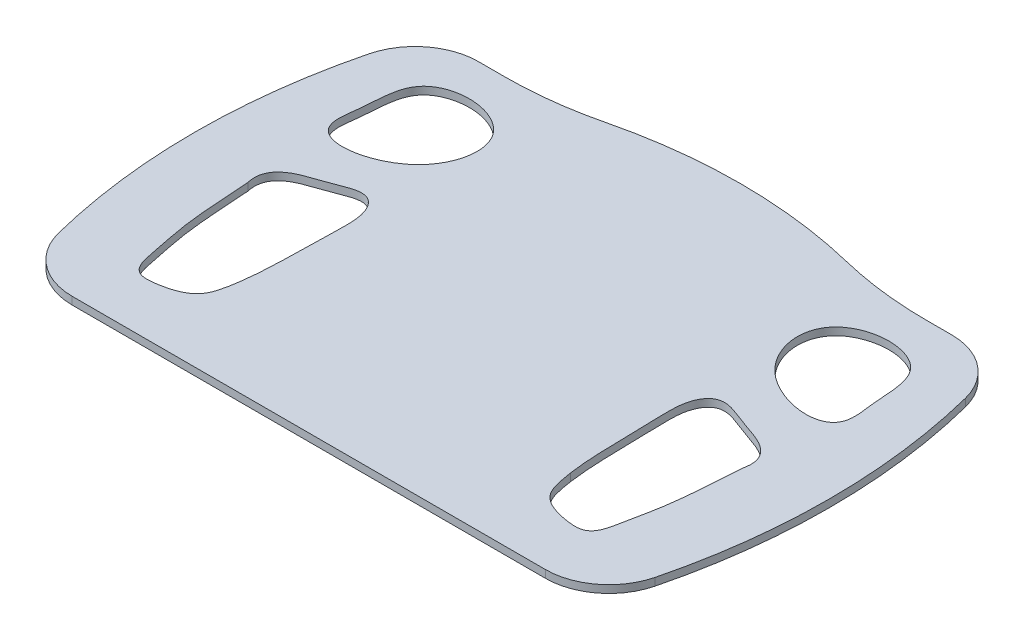
SolidWorks part; units mm, degrees
ref_plane "前视基准面" through (0, 0, 0) normal (0, 0, 1) x (1, 0, 0)
ref_plane "上视基准面" through (0, 0, 0) normal (0, 1, 0) x (1, 0, 0)
ref_plane "右视基准面" through (0, 0, 0) normal (1, 0, 0) x (0, 0, -1)
other "Configuration Table"
sketch "草图1" plane through (0, 0, 0) normal (0, 1, 0) x (1, 0, 0)
  line L0 (94.3902, -85.9727) -> (-91.9583, -85.9727)
  line L1 (-91.9583, 74.0273) -> (-81.8503, 74.0273)
  line L2 (84.2822, 74.0273) -> (94.3902, 74.0273)
  arc A0 (94.3902, -85.9727) -> (118.6318, -67.0839) centre (94.3902, -60.9727) ccw
  arc A1 (-116.1999, -67.0839) -> (-91.9583, -85.9727) centre (-91.9583, -60.9727) ccw
  arc A2 (-116.1999, 55.1384) -> (-116.1999, -67.0839) centre (126.2159, -5.9727) ccw
  arc A3 (-91.9583, 74.0273) -> (-116.1999, 55.1384) centre (-91.9583, 49.0273) ccw
  arc A4 (-81.8503, 74.0273) -> (-46.2505, 78.313) centre (-81.8503, 224.0273) ccw
  arc A5 (48.6824, 78.313) -> (-46.2505, 78.313) centre (1.2159, -115.9727) ccw
  arc A6 (48.6824, 78.313) -> (84.2822, 74.0273) centre (84.2822, 224.0273) ccw
  arc A7 (118.6318, 55.1384) -> (94.3902, 74.0273) centre (94.3902, 49.0273) ccw
  arc A8 (118.6318, -67.0839) -> (118.6318, 55.1384) centre (-123.7841, -5.9727) ccw
  spline S0 degree 3 poles (66.2811, 20.5807) (60.5847, 52.9198) (82.8802, 61.3288) (95.3724, 57.693) (102.1843, 48.7306) (101.6256, 38.7803) (103.3639, 27.4794) (102.123, 14.4904) (66.2811, 20.5807) (60.5847, 52.9198) (82.8802, 61.3288) knots -0.58846 -0.515599 -0.249223 0 0.116916 0.219737 0.24839 0.386216 0.41154 0.484401 0.750777 1 1.116916 1.219737 1.24839 only from (68.9861, 54.0529) to (68.9861, 54.0529)
  spline S1 degree 3 poles (66.3784, -48.0704) (66.5131, -48.9639) (66.7845, -50.7507) (67.2066, -52.9697) (67.6381, -54.7261) (68.0285, -56.0263) (68.5147, -57.2927) (69.1248, -58.5037) (69.878, -59.6297) (70.7809, -60.64) (71.6384, -61.376) (72.373, -61.9014) (72.945, -62.265) (73.5345, -62.5993) (74.1387, -62.9062) (74.7553, -63.1874) (75.3821, -63.4451) (76.0175, -63.6812) (76.8741, -63.9697) (77.9594, -64.2861) (79.0571, -64.5561) (79.9401, -64.7497) (80.6044, -64.8843) (81.2708, -65.0088) (82.1619, -65.1601) (83.0572, -65.2868) (83.9569, -65.3776) (84.6336, -65.4235) (85.3116, -65.4416) (85.9897, -65.4257) (86.6662, -65.3691) (87.3361, -65.2628) (87.9925, -65.0972) (88.6273, -64.8628) (89.2293, -64.5525) (89.6934, -64.2311) (90.0376, -63.9398) (90.363, -63.6276) (90.8818, -63.0312) (91.4805, -62.067) (92.0221, -60.8229) (92.4404, -59.5318) (92.7821, -58.2197) (93.0753, -56.8962) (93.2981, -55.7889) (93.4711, -54.9021) (93.5994, -54.2368) (93.7276, -53.5715) (93.8995, -52.6847) (94.1177, -51.5768) (94.4754, -49.8059) (94.931, -47.594) (95.4557, -44.9353) (95.9298, -42.2673) (96.3444, -39.5896) (96.7029, -36.9039) (96.9861, -34.4363) (97.1669, -32.6388) (97.3141, -31.0649) (97.529, -28.5902) (97.7934, -24.9862) (98.044, -21.1547) (98.2513, -17.9996) (98.4386, -15.2962) (98.5686, -13.4942) (98.6335, -12.5933) knots 0 0 0 0 0.03125 0.0625 0.078125 0.09375 0.109375 0.125 0.140625 0.15625 0.171875 0.179688 0.1875 0.195312 0.203125 0.210938 0.21875 0.226562 0.234375 0.25 0.265625 0.273438 0.28125 0.289062 0.296875 0.3125 0.320312 0.328125 0.335938 0.34375 0.351562 0.359375 0.367188 0.375 0.382812 0.390625 0.394531 0.398438 0.40625 0.421875 0.4375 0.453125 0.46875 0.484375 0.5 0.507812 0.515625 0.523438 0.53125 0.546875 0.5625 0.59375 0.625 0.65625 0.6875 0.71875 0.75 0.773438 0.78125 0.804688 0.859375 0.90625 0.9375 0.96875 1 1 1 1
  spline S2 degree 3 poles (98.6335, -12.5933) (98.658, -12.4729) (98.7068, -12.2321) (98.7991, -11.7494) (98.932, -10.899) (99.0019, -9.916) (98.9726, -8.9343) (98.8963, -8.2016) (98.7626, -7.4772) (98.5696, -6.7666) (98.3164, -6.0754) (97.8997, -5.1872) (96.9698, -3.7368) (95.5452, -2.3612) (93.9275, -1.2417) (92.6468, -0.5102) (91.319, 0.1292) (89.9592, 0.6951) (88.5772, 1.208) (87.415, 1.609) (86.4833, 1.9246) (85.7848, 2.1613) (85.2038, 2.3607) (84.7398, 2.5224) (84.2766, 2.6858) (83.6987, 2.893) (83.1227, 3.1049) (82.6629, 3.2774) (82.2039, 3.4517) (81.6312, 3.6727) (80.9451, 3.9412) (80.2596, 4.2113) (79.5736, 4.4809) (78.8862, 4.7474) (78.1964, 5.008) (77.5029, 5.2587) (76.8046, 5.4946) (76.1002, 5.7108) (75.3886, 5.902) (74.6688, 6.0625) (74.0619, 6.1644) (73.5734, 6.2218) (73.2059, 6.2516) (72.8379, 6.2667) (72.4699, 6.266) (72.1025, 6.248) (71.7366, 6.2115) (71.3732, 6.1555) (70.8938, 6.0534) (70.3073, 5.8723) (69.6355, 5.5695) (68.797, 5.0575) (67.8802, 4.2331) (67.1348, 3.2498) (66.6301, 2.4076) (66.2942, 1.7515) (65.9978, 1.0768) (65.7379, 0.3875) (65.5126, -0.3139) (65.3198, -1.0251) (65.1575, -1.7439) (65.0239, -2.468) (64.9163, -3.1963) (64.8043, -4.1716) (64.7339, -5.1518) (64.6941, -6.1344) (64.6768, -6.8719) (64.6693, -7.6096) (64.6692, -8.3471) (64.6743, -9.0843) (64.6829, -9.8213) (64.6936, -10.5581) (64.7099, -11.5404) (64.7322, -12.7681) (64.8089, -16.6965) (64.9014, -20.624) (64.9962, -24.5517) (65.0381, -26.27) (65.0747, -27.7429) (65.1124, -29.2158) (65.1578, -30.9342) (65.2284, -33.3889) (65.3408, -36.3338) (65.4978, -39.2767) (65.713, -42.2155) (65.9517, -44.6593) (66.1852, -46.6097) (66.314, -47.5835) (66.3784, -48.0704) knots 0 0 0 0 0.003906 0.007812 0.015625 0.03125 0.039062 0.046875 0.054688 0.0625 0.070312 0.078125 0.09375 0.125 0.140625 0.15625 0.171875 0.1875 0.203125 0.21875 0.226562 0.234375 0.242188 0.246094 0.25 0.257812 0.265625 0.269531 0.273438 0.28125 0.289062 0.296875 0.304688 0.3125 0.320312 0.328125 0.335938 0.34375 0.351562 0.359375 0.367188 0.371094 0.375 0.378906 0.382812 0.386719 0.390625 0.394531 0.398438 0.40625 0.414062 0.421875 0.4375 0.453125 0.460938 0.46875 0.476562 0.484375 0.492188 0.5 0.507812 0.515625 0.523438 0.53125 0.546875 0.554688 0.5625 0.570312 0.578125 0.585938 0.59375 0.601562 0.609375 0.625 0.640625 0.734375 0.75 0.765625 0.789062 0.796875 0.8125 0.84375 0.875 0.90625 0.9375 0.96875 0.984375 1 1 1 1
  spline S3 degree 3 poles (-63.3302, 20.5807) (-57.6337, 52.9198) (-79.9293, 61.3288) (-92.4214, 57.693) (-99.2334, 48.7306) (-98.6747, 38.7803) (-100.4129, 27.4794) (-99.172, 14.4904) (-63.3302, 20.5807) (-57.6337, 52.9198) (-79.9293, 61.3288) knots -0.58846 -0.515599 -0.249223 0 0.116916 0.219737 0.24839 0.386216 0.41154 0.484401 0.750777 1 1.116916 1.219737 1.24839 only from (-66.0351, 54.0529) to (-66.0351, 54.0529)
  spline S4 degree 3 poles (-96.2016, -12.5933) (-96.0705, -14.3951) (-95.8118, -17.999) (-95.4676, -23.408) (-95.0892, -28.8158) (-94.6022, -34.2141) (-94.0503, -38.6968) (-93.4968, -42.2671) (-93.0238, -44.9353) (-92.5871, -47.151) (-92.2263, -48.9213) (-91.9546, -50.2488) (-91.6862, -51.5769) (-91.4243, -52.9063) (-91.1673, -54.2368) (-90.9536, -55.3457) (-90.777, -56.2317) (-90.64, -56.8953) (-90.4961, -57.5575) (-90.343, -58.2176) (-90.178, -58.8752) (-89.9982, -59.5293) (-89.8323, -60.0699) (-89.6871, -60.4982) (-89.5325, -60.9233) (-89.32, -61.4473) (-89.0276, -62.0591) (-88.6909, -62.6473) (-88.3677, -63.1098) (-88.0808, -63.4576) (-87.8509, -63.7058) (-87.6065, -63.9397) (-87.348, -64.1578) (-87.0762, -64.3587) (-86.6972, -64.6025) (-86.1957, -64.8604) (-85.561, -65.0954) (-84.6856, -65.3178) (-83.5583, -65.4458) (-82.1998, -65.4349) (-80.8486, -65.3149) (-79.5061, -65.1275) (-78.3941, -64.9289) (-77.5083, -64.7489) (-76.625, -64.5558) (-75.7467, -64.3406) (-74.8762, -64.0967) (-74.228, -63.8979) (-73.5856, -63.6813) (-72.9501, -63.445) (-72.3231, -63.1871) (-71.5005, -62.8118) (-70.5031, -62.2789) (-69.3776, -61.5229) (-68.3488, -60.64) (-67.5968, -59.7982) (-67.0696, -59.0666) (-66.5911, -58.3017) (-66.1846, -57.4945) (-65.8407, -56.6593) (-65.6104, -56.0216) (-65.4037, -55.3751) (-65.1548, -54.5048) (-64.8839, -53.4077) (-64.6067, -52.0816) (-64.365, -50.7485) (-64.1485, -49.4106) (-64.0138, -48.5171) (-63.9465, -48.0704) knots 0 0 0 0 0.0625 0.125 0.1875 0.25 0.3125 0.34375 0.375 0.40625 0.421875 0.4375 0.453125 0.46875 0.484375 0.5 0.507812 0.515625 0.523438 0.53125 0.539062 0.546875 0.554688 0.558594 0.5625 0.570312 0.578125 0.585938 0.59375 0.597656 0.601562 0.605469 0.609375 0.613281 0.617188 0.625 0.632812 0.640625 0.65625 0.671875 0.6875 0.703125 0.71875 0.726562 0.734375 0.75 0.757812 0.765625 0.773438 0.78125 0.789062 0.796875 0.8125 0.828125 0.84375 0.859375 0.867188 0.875 0.890625 0.898438 0.90625 0.914062 0.921875 0.9375 0.953125 0.96875 0.984375 1 1 1 1
  spline S5 degree 3 poles (-63.9465, -48.0704) (-63.6819, -46.1237) (-63.233, -42.2195) (-62.9516, -37.3146) (-62.7988, -33.3889) (-62.6836, -29.4614) (-62.5661, -24.5516) (-62.4255, -18.6599) (-62.3184, -13.75) (-62.2563, -10.3127) (-62.2361, -8.3477) (-62.2422, -6.3812) (-62.3263, -4.4163) (-62.5787, -2.4664) (-62.8234, -1.2614) (-63.0803, -0.3127) (-63.3054, 0.3888) (-63.5653, 1.078) (-63.862, 1.7522) (-64.142, 2.2986) (-64.3871, 2.7243) (-64.6468, 3.1415) (-64.9997, 3.6452) (-65.9412, 4.7804) (-67.3722, 5.8053) (-69.3001, 6.2596) (-70.7758, 6.2878) (-71.9969, 6.1164) (-72.9565, 5.9019) (-73.6682, 5.7097) (-74.3726, 5.4926) (-75.071, 5.2563) (-75.7645, 5.006) (-76.6845, 4.6601) (-77.8284, 4.2128) (-79.1988, 3.6713) (-80.5744, 3.144) (-82.4197, 2.4711) (-84.2841, 1.8479) (-86.1443, 1.2071) (-87.527, 0.6944) (-88.8871, 0.129) (-90.2145, -0.5102) (-91.4944, -1.2414) (-92.708, -2.0819) (-93.8243, -3.0482) (-95.1346, -4.518) (-96.0623, -6.2738) (-96.4926, -8.1972) (-96.5726, -9.425) (-96.537, -10.4084) (-96.4766, -11.0206) (-96.4073, -11.5073) (-96.3249, -11.9917) (-96.2515, -12.3528) (-96.2016, -12.5933) knots 0 0 0 0 0.0625 0.125 0.15625 0.1875 0.25 0.3125 0.375 0.40625 0.421875 0.4375 0.46875 0.484375 0.5 0.507812 0.515625 0.523438 0.53125 0.539062 0.542969 0.546875 0.554688 0.5625 0.59375 0.609375 0.625 0.640625 0.648438 0.65625 0.664062 0.671875 0.679688 0.6875 0.703125 0.71875 0.734375 0.75 0.78125 0.796875 0.8125 0.828125 0.84375 0.859375 0.875 0.890625 0.90625 0.9375 0.953125 0.96875 0.976562 0.984375 0.988281 0.992188 1 1 1 1
extrude "凸台-拉伸1" add sketch "草图1" along normal blind 3
